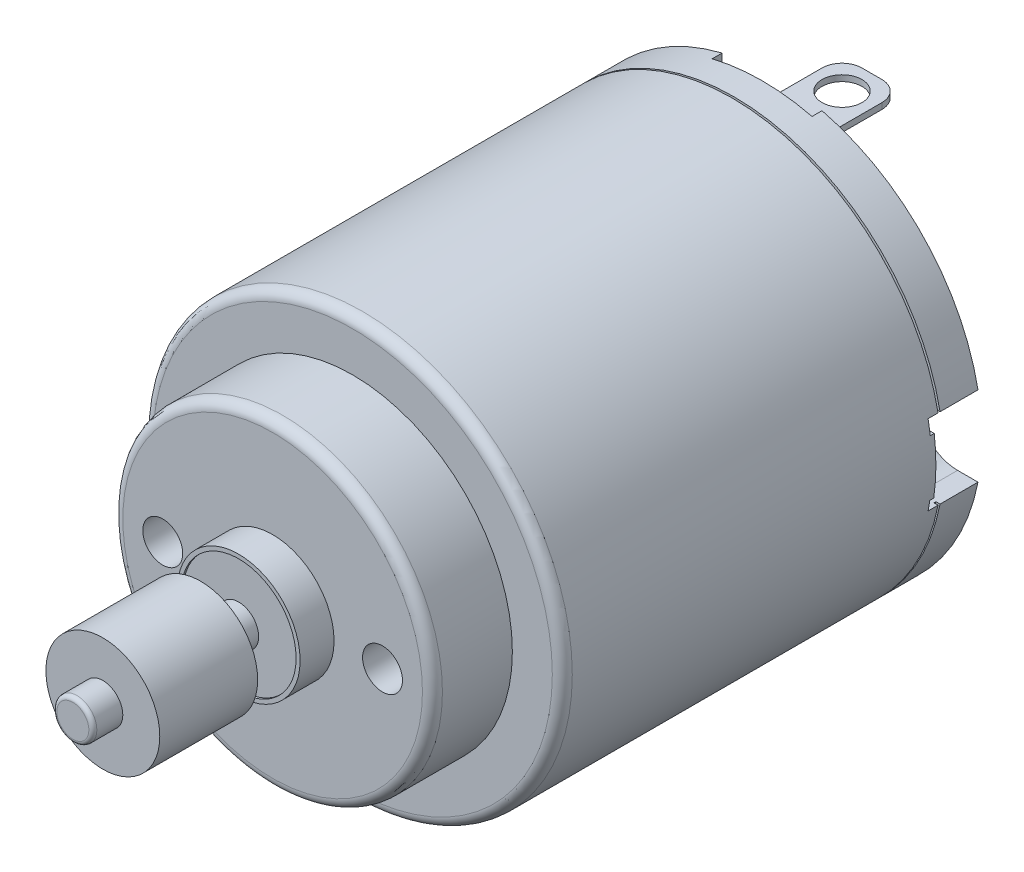
SolidWorks part; units mm, degrees
ref_plane "Plano frontal" through (0, 0, 0) normal (0, 0, 1) x (1, 0, 0)
ref_plane "Plano superior" through (0, 0, 0) normal (0, 1, 0) x (1, 0, 0)
ref_plane "Plano direito" through (0, 0, 0) normal (1, 0, 0) x (0, 0, -1)
sketch "Esboço1" plane through (0, 0, 0) normal (0, 0, 1) x (1, 0, 0)
  circle A0 centre (0, 0) radius 1
  dimension "D1" = 2
extrude "Ressalto-extrusão1" add sketch "Esboço1" along normal blind 38
ref_plane "Plano1" through (0, 0, 28) normal (0, 0, 1) x (1, 0, 0)
sketch "Esboço2" plane through (0, 0, 28) normal (0, 0, 1) x (1, 0, 0)
  circle A0 centre (0, 0) radius 8
  dimension "D1" = 16
extrude "Ressalto-extrusão2" add sketch "Esboço2" against normal blind 25
sketch "Esboço3" plane through (0, 0, 28) normal (0, 0, 1) x (1, 0, 0)
  circle A0 centre (0, 0) radius 3.075
  dimension "D1" = 6.15
extrude "Ressalto-extrusão3" add sketch "Esboço3" along normal blind 1.7
sketch "Esboço4" plane through (0, 0, 3) normal (0, 0, -1) x (-1, 0, 0)
  circle A0 centre (0, 0) radius 10.5
  dimension "D1" = 21
extrude "Ressalto-extrusão4" add sketch "Esboço4" against normal blind 21
sketch "Esboço5" plane through (0, 0, 3) normal (0, 0, -1) x (-1, 0, 0)
  circle A0 centre (0, 0) radius 3.125
  dimension "D1" = 6.25
extrude "Ressalto-extrusão5" add sketch "Esboço5" along normal blind 2
sketch "Esboço6" plane through (0, 0, 3) normal (0, 0, -1) x (-1, 0, 0)
  line L0 (0, 10.5) -> (0, -10.5) construction
  line L2 (1.5, 8.05) -> (-1.5, 8.05)
  line L3 (1.5, 8.05) -> (1.5, 7.75)
  line L4 (1.5, 7.75) -> (-1.5, 7.75)
  line L5 (-1.5, 8.05) -> (-1.5, 7.75)
  line L6 (1.5, 8.05) -> (-1.5, 7.75) construction
  line L7 (1.5, 7.75) -> (-1.5, 8.05) construction
  line L8 (1.5, -7.75) -> (-1.5, -7.75)
  line L9 (1.5, -7.75) -> (1.5, -8.05)
  line L10 (1.5, -8.05) -> (-1.5, -8.05)
  line L11 (-1.5, -7.75) -> (-1.5, -8.05)
  line L12 (1.5, -7.75) -> (-1.5, -8.05) construction
  line L13 (1.5, -8.05) -> (-1.5, -7.75) construction
  circle A0 centre (0, 0) radius 10.5 construction
  point P5 (0, 7.9)
  point P10 (0, -7.9)
  dimension "D1" = 15.5
  dimension "D2" = 0.3
  dimension "D3" = 0.3
  dimension "D4" = 3
  dimension "D5" = 3
  dimension "D6" = 7.75
extrude "Ressalto-extrusão6" add sketch "Esboço6" along normal blind 5
sketch "Esboço7" plane through (0, 8.05, 0) normal (0, 1, 0) x (1, 0, 0)
  line L0 (-1.5, 2) -> (1.5, 2) construction
  circle A0 centre (0, 0.5) radius 1
  dimension "D1" = 2
  dimension "D2" = 1.5
extrude "Corte-extrusão1" cut sketch "Esboço7" against normal blind 4
sketch "Esboço8" plane through (0, -7.75, 0) normal (0, 1, 0) x (1, 0, 0)
  circle A0 centre (0, 0.5) radius 1
extrude "Corte-extrusão2" cut sketch "Esboço8" against normal blind 4
fillet "Filete1" radius 1 4 edges at (1.5, -7.9, -2) (-1.5, -7.9, -2) (1.5, 7.9, -2) (-1.5, 7.9, -2)
fillet "Filete2" radius 0.2 2 edges at (1, 0, 0) (1, 0, 38)
sketch "Esboço9" plane through (0, 0, 3) normal (0, 0, -1) x (-1, 0, 0)
  circle A0 centre (-5.5, 0) radius 1
  circle A1 centre (5.5, 0) radius 1
  dimension "D1" = 11
  dimension "D3" = 2
  dimension "D4" = 2
  dimension "D2" = 5.5
extrude "Corte-extrusão3" cut sketch "Esboço9" against normal blind 38 and the other way blind 15
sketch "Esboço10" plane through (0, 0, 1) normal (0, 0, -1) x (-1, 0, 0)
  line L0 (2.575, 4.4181) -> (2.575, -4.909) construction
  line L2 (2.575, 4.4181) -> (2.575, -4.909)
  line L3 (2.575, -4.909) -> (3.8141, -4.909)
  line L4 (3.8141, -4.909) -> (3.8141, 4.4181)
  line L5 (3.8141, 4.4181) -> (2.575, 4.4181)
extrude "Corte-extrusão4" cut sketch "Esboço10" against normal blind 2
sketch "Esboço11" plane through (0, 0, 3) normal (0, 0, -1) x (-1, 0, 0)
  line L0 (-3.7081, 1.5) -> (-7.3485, 1.5)
  line L1 (7.3485, 1.5) -> (3.7081, 1.5)
  line L3 (7.3485, -1.5) -> (3.7081, -1.5)
  line L5 (-2.5, -7.0711) -> (-2.5, -12.5)
  line L6 (2.5, -7.0711) -> (2.5, -12.5)
  line L7 (-3.7081, -1.5) -> (-7.3485, -1.5)
  line L9 (2.5, 12.5) -> (-2.5, 12.5)
  line L10 (2.5, 12.5) -> (2.5, 7.0711)
  line L11 (2.5, -12.5) -> (-2.5, -12.5)
  line L12 (-2.5, 12.5) -> (-2.5, 7.0711)
  arc A0 (-7.3485, -1.5) -> (-2.5, -7.0711) centre (0, 0) ccw
  circle A1 centre (0, 0) radius 10.5 construction
  arc A2 (-3.7081, -1.5) -> (-2.5, -3.1225) centre (0, 0) ccw
  arc A3 (7.3485, 1.5) -> (2.5, 7.0711) centre (0, 0) ccw
  arc A4 (3.7081, 1.5) -> (2.5, 3.1225) centre (0, 0) ccw
  arc A5 (-2.5, 7.0711) -> (-7.3485, 1.5) centre (0, 0) ccw
  arc A6 (2.5, 3.1225) -> (-3.7081, 1.5) centre (0, 0) ccw
  arc A7 (2.5, -7.0711) -> (7.3485, -1.5) centre (0, 0) ccw
  arc A8 (-2.5, -3.1225) -> (3.7081, -1.5) centre (0, 0) ccw
  point P0 (0, 0)
  dimension "D2" = 3
  dimension "D3" = 8
  dimension "D1" = 5
  dimension "D4" = 25
extrude "Corte-extrusão5" cut sketch "Esboço11" against normal blind 0.5
sketch "Esboço12" plane through (0, 0, 3.5) normal (0, 0, -1) x (-1, 0, 0)
  line L0 (0, 0) -> (0, -6.6243) construction
  line L2 (0, 0) -> (13.3788, 0) construction
  arc A0 (3.375, -5.8457) -> (5.8457, -3.375) centre (0, 0) ccw
  arc A1 (2.375, -4.1136) -> (4.1136, -2.375) centre (0, 0) ccw
  arc A2 (2.375, -4.1136) -> (3.375, -5.8457) centre (2.875, -4.9796) ccw
  arc A3 (4.1136, -2.375) -> (5.8457, -3.375) centre (4.9796, -2.875) cw
  arc A8 (-3.375, 5.8457) -> (-5.8457, 3.375) centre (0, 0) ccw
  arc A9 (-4.1136, 2.375) -> (-5.8457, 3.375) centre (-4.9796, 2.875) cw
  arc A10 (-2.375, 4.1136) -> (-4.1136, 2.375) centre (0, 0) ccw
  arc A11 (-2.375, 4.1136) -> (-3.375, 5.8457) centre (-2.875, 4.9796) ccw
  dimension "D1" = 13.5
  dimension "D2" = 9.5
extrude "Corte-extrusão6" cut sketch "Esboço12" against normal blind 2
sketch "Esboço13" plane through (0, 0, 3) normal (0, 0, 1) x (1, 0, 0)
  line L1 (1.5, 8.05) -> (-1.5, 8.05)
  line L2 (1.5, 8.05) -> (1.5, 7.75)
  line L3 (1.5, 7.75) -> (-1.5, 7.75)
  line L4 (-1.5, 8.05) -> (-1.5, 7.75)
  line L5 (-1.5, -8.05) -> (1.5, -8.05)
  line L6 (-1.5, -8.05) -> (-1.5, -7.75)
  line L7 (-1.5, -7.75) -> (1.5, -7.75)
  line L8 (1.5, -8.05) -> (1.5, -7.75)
extrude "Ressalto-extrusão7" add sketch "Esboço13" along normal blind 6
ref_plane "Plano2" through (0, 0, 5) normal (0, 0, -1) x (-1, 0, 0)
sketch "Esboço14" plane through (0, 0, 5) normal (0, 0, -1) x (-1, 0, 0)
  circle A0 centre (0, 0) radius 11.3093
  circle A1 centre (0, 0) radius 10.3
  arc A2 (-2.5, 10.198) -> (-2.5, -10.198) centre (0, 0) ccw construction
  dimension "D1" = 0.2
extrude "Corte-extrusão7" cut sketch "Esboço14" along normal blind 0.1
fillet "Filete3" radius 0.5 2 edges at (8, 0, 28) (-10.5, 0, 24)
sketch "Esboço15" plane through (0, 0, 29.7) normal (0, 0, 1) x (1, 0, 0)
  circle A0 centre (0, 0) radius 2.875
  circle A1 centre (0, 0) radius 3.075 construction
  dimension "D1" = 0.2
extrude "Corte-extrusão8" cut sketch "Esboço15" against normal blind 0.1
sketch "Esboço16" plane through (0, 0, 3) normal (0, 0, -1) x (-1, 0, 0)
  line L0 (-9.2871, 2) -> (-10.3078, 2)
  line L1 (10.3078, 2) -> (9.2871, 2)
  line L3 (10.3078, -2) -> (9.2871, -2)
  line L7 (-9.2871, -2) -> (-10.3078, -2)
  arc A0 (-2.5, 10.198) -> (-2.5, -10.198) centre (0, 0) ccw construction
  arc A3 (-9.2871, -2) -> (-9.2871, 2) centre (-9.2871, 0) ccw
  arc A4 (9.2871, 2) -> (9.2871, -2) centre (9.2871, 0) ccw
  arc A5 (-10.3078, 2) -> (-10.3078, -2) centre (0, 0) ccw
  arc A6 (10.3078, -2) -> (10.3078, 2) centre (0, 0) ccw
  point P0 (0, 0)
  dimension "D1" = 4
extrude "Corte-extrusão9" cut sketch "Esboço16" against normal blind 2.5
sketch "Esboço17" plane through (0, 0, 5.5) normal (0, 0, -1) x (-1, 0, 0)
  line L0 (-8.5973, 1.3172) -> (-10.417, 1.3172)
  line L1 (10.417, 1.3172) -> (8.5973, 1.3172)
  line L2 (10.417, -1.3172) -> (10.417, -1.5)
  line L3 (10.417, -1.5) -> (8.5666, -1.5)
  line L5 (8.3688, -1.3) -> (8.3951, 1.1172)
  line L6 (10.417, -1.5) -> (10.3928, -1.4965) construction
  line L7 (-8.5973, 1.3172) -> (-8.3951, 1.1172)
  line L8 (-8.3688, -1.3) -> (-8.5666, -1.5)
  line L9 (-8.5666, -1.5) -> (-10.3923, -1.5)
  line L10 (-8.3951, 1.1172) -> (-8.3688, -1.3)
  line L11 (8.5666, -1.5) -> (8.3688, -1.3)
  line L12 (8.5973, 1.3172) -> (8.3951, 1.1172)
  arc A0 (-10.417, 1.3172) -> (-10.3923, -1.5) centre (0, 0) ccw
  arc A2 (10.3923, -1.5) -> (10.417, 1.3172) centre (0, 0) ccw
  point P0 (0, 0)
  point P6 (8.3973, 1.3172)
  point P11 (-8.3973, 1.3172)
  point P13 (-8.3666, -1.5)
  point P14 (8.3666, -1.5)
  arc M6 (-10.3078, 2) -> (-10.3078, -2) centre (0, 0) ccw
extrude "Ressalto-extrusão8" add sketch "Esboço17" along normal blind 0.2 contours L3 A2 L1 L12 L5 L11 | L10 L7 L0 L9 L8 M6
ref_plane "Plano3" through (0, 0, 36.5) normal (0, 0, 1) x (1, 0, 0)
sketch "Esboço18" plane through (0, 0, 36.5) normal (0, 0, 1) x (1, 0, 0)
  circle A0 centre (0, 0) radius 2.85
  dimension "D1" = 5.7
extrude "Ressalto-extrusão9" add sketch "Esboço18" against normal blind 4.9
